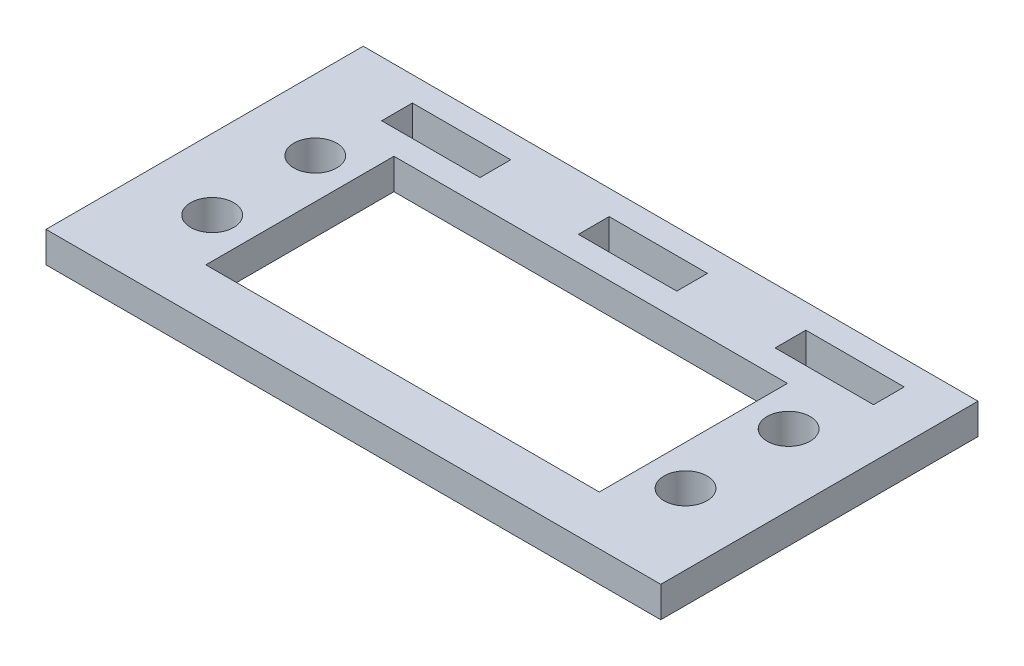
SolidWorks part; units mm, degrees
ref_plane "Front Plane" through (0, 0, 0) normal (0, 0, 1) x (1, 0, 0)
ref_plane "Top Plane" through (0, 0, 0) normal (0, 1, 0) x (1, 0, 0)
ref_plane "Right Plane" through (0, 0, 0) normal (1, 0, 0) x (0, 0, -1)
sketch "Sketch1" plane through (0, 0, 0) normal (0, 1, 0) x (1, 0, 0)
  line L0 (26.67, -9.7155) -> (31.75, -9.7155) construction
  line L1 (31.75, 17.9705) -> (-31.75, 17.9705)
  line L2 (31.75, 17.9705) -> (31.75, -14.7955)
  line L3 (31.75, -14.7955) -> (-31.75, -14.7955)
  line L4 (-31.75, 17.9705) -> (-31.75, -14.7955)
  line L5 (26.67, -9.7155) -> (26.67, -14.7955) construction
  line L6 (-26.67, -9.7155) -> (-31.75, -9.7155) construction
  line L7 (-26.67, 9.7155) -> (26.67, 9.7155) construction
  line L8 (-26.67, 9.7155) -> (-26.67, -9.7155) construction
  line L9 (-26.67, -9.7155) -> (26.67, -9.7155) construction
  line L10 (26.67, 9.7155) -> (26.67, -9.7155) construction
  line L11 (-26.67, 9.7155) -> (26.67, -9.7155) construction
  line L12 (-26.67, -9.7155) -> (26.67, 9.7155) construction
  line L13 (26.67, 15.4305) -> (26.67, 17.9705) construction
  line L14 (26.67, 15.4305) -> (16.51, 15.4305)
  line L15 (26.67, 15.4305) -> (26.67, 12.2555)
  line L16 (26.67, 12.2555) -> (16.51, 12.2555)
  line L17 (16.51, 15.4305) -> (16.51, 12.2555)
  line L18 (26.67, 15.4305) -> (16.51, 12.2555) construction
  line L19 (26.67, 12.2555) -> (16.51, 15.4305) construction
  line L20 (26.67, 12.2555) -> (26.67, 9.7155) construction
  line L21 (6.35, 15.4305) -> (6.35, 12.2555)
  line L22 (6.35, 15.4305) -> (-3.81, 15.4305)
  line L23 (6.35, 12.2555) -> (-3.81, 12.2555)
  line L24 (-3.81, 15.4305) -> (-3.81, 12.2555)
  line L25 (-13.97, 15.4305) -> (-13.97, 12.2555)
  line L26 (-13.97, 15.4305) -> (-24.13, 15.4305)
  line L27 (-13.97, 12.2555) -> (-24.13, 12.2555)
  line L28 (-24.13, 15.4305) -> (-24.13, 12.2555)
  line L30 (-20.32, -9.7155) -> (20.32, -9.7155)
  line L31 (-20.32, -9.7155) -> (-20.32, 9.7155)
  line L32 (-20.32, 9.7155) -> (20.32, 9.7155)
  line L33 (20.32, -9.7155) -> (20.32, 9.7155)
  line L34 (-20.32, -9.7155) -> (20.32, 9.7155) construction
  line L35 (-20.32, 9.7155) -> (20.32, -9.7155) construction
  circle A0 centre (-24.4475, 5.7119) radius 2.2225
  circle A1 centre (-24.4475, -4.935) radius 2.2225
  circle A2 centre (24.4475, 5.7119) radius 2.2225
  circle A3 centre (24.4475, -4.935) radius 2.2225
  point P0 (0, 0)
  point P4 (21.59, 13.843)
  point P6 (0, 0)
  point P20 (0, 0)
  dimension "D9" = 4.445
  dimension "D1" = 19.431
  dimension "D2" = 53.34
  dimension "D3" = 5.08
  dimension "D4" = 3.175
  dimension "D5" = 10.16
  dimension "D6" = 2.54
  dimension "D7" = 3
  dimension "D8" = 6.35
extrude "Boss-Extrude2" add sketch "Sketch1" along normal blind 3.175
sketch "Sketch2" plane through (0, 3.175, 0) normal (0, 1, 0) x (1, 0, 0)
  line L8 (31.8262, 18.0467) -> (-31.8262, 18.0467)
  line L9 (31.8262, -14.8717) -> (31.8262, 18.0467)
  line L10 (-31.8262, -14.8717) -> (31.8262, -14.8717)
  line L11 (-31.8262, 18.0467) -> (-31.8262, -14.8717)
  line L12 (31.8262, 18.0467) -> (-31.8262, 18.0467)
  line L13 (31.8262, -14.8717) -> (31.8262, 18.0467)
  line L14 (-31.8262, -14.8717) -> (31.8262, -14.8717)
  line L15 (-31.8262, 18.0467) -> (-31.8262, -14.8717)
  line L16 (-20.32, 9.7155) -> (-20.32, -9.7155)
  line L17 (-20.32, -9.7155) -> (20.32, -9.7155)
  line L18 (20.32, -9.7155) -> (20.32, 9.7155)
  line L19 (20.32, 9.7155) -> (-20.32, 9.7155)
  line L20 (-24.0538, 15.3543) -> (-24.0538, 12.3317)
  line L21 (-14.0462, 15.3543) -> (-24.0538, 15.3543)
  line L22 (-14.0462, 12.3317) -> (-14.0462, 15.3543)
  line L23 (-24.0538, 12.3317) -> (-14.0462, 12.3317)
  line L24 (-24.0538, 15.3543) -> (-24.0538, 12.3317)
  line L25 (-14.0462, 15.3543) -> (-24.0538, 15.3543)
  line L26 (-14.0462, 12.3317) -> (-14.0462, 15.3543)
  line L27 (-24.0538, 12.3317) -> (-14.0462, 12.3317)
  line L28 (-20.32, 9.7155) -> (-20.32, -9.7155)
  line L29 (-20.32, -9.7155) -> (20.32, -9.7155)
  line L30 (20.32, -9.7155) -> (20.32, 9.7155)
  line L31 (20.32, 9.7155) -> (-20.32, 9.7155)
  line L32 (-3.7338, 15.3543) -> (-3.7338, 12.3317)
  line L33 (6.2738, 15.3543) -> (-3.7338, 15.3543)
  line L34 (6.2738, 12.3317) -> (6.2738, 15.3543)
  line L35 (-3.7338, 12.3317) -> (6.2738, 12.3317)
  line L36 (-3.7338, 15.3543) -> (-3.7338, 12.3317)
  line L37 (6.2738, 15.3543) -> (-3.7338, 15.3543)
  line L38 (6.2738, 12.3317) -> (6.2738, 15.3543)
  line L39 (-3.7338, 12.3317) -> (6.2738, 12.3317)
  line L44 (26.5938, 12.3317) -> (26.5938, 15.3543)
  line L45 (26.5938, 15.3543) -> (16.5862, 15.3543)
  line L46 (16.5862, 15.3543) -> (16.5862, 12.3317)
  line L47 (16.5862, 12.3317) -> (26.5938, 12.3317)
  line L48 (26.5938, 12.3317) -> (26.5938, 15.3543)
  line L49 (26.5938, 15.3543) -> (16.5862, 15.3543)
  line L50 (16.5862, 15.3543) -> (16.5862, 12.3317)
  line L51 (16.5862, 12.3317) -> (26.5938, 12.3317)
  circle A2 centre (-24.4475, 5.7119) radius 2.1463
  circle A3 centre (-24.4475, 5.7119) radius 2.1463
  circle A5 centre (-24.4475, -4.935) radius 2.1463
  circle A6 centre (-24.4475, -4.935) radius 2.1463
  circle A8 centre (24.4475, 5.7119) radius 2.1463
  circle A9 centre (24.4475, 5.7119) radius 2.1463
  circle A11 centre (24.4475, -4.935) radius 2.1463
  circle A12 centre (24.4475, -4.935) radius 2.1463
  dimension "D1" = 0.0762
  dimension "D2" = 0.0762
  dimension "D3" = 0.0762
  dimension "D4" = 0.0762
  dimension "D5" = 0.0762
  dimension "D6" = 0.0762
  dimension "D7" = 0.0762
  dimension "D8" = 0.0762
  dimension "D9" = 0
